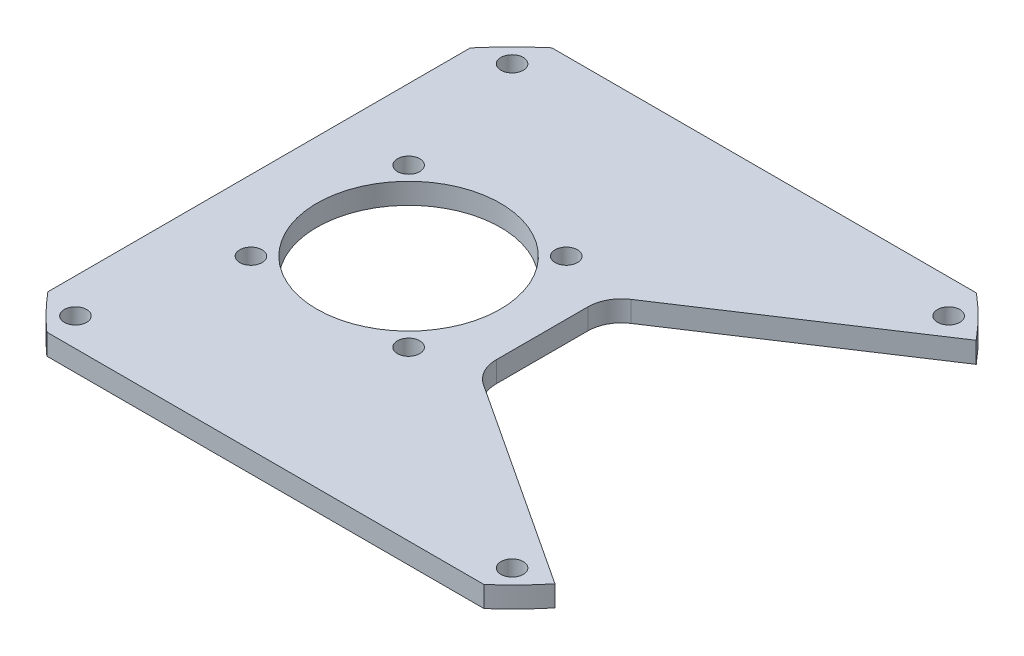
SolidWorks part; units mm, degrees
ref_plane "Front Plane" through (0, 0, 0) normal (0, 0, 1) x (1, 0, 0)
ref_plane "Top Plane" through (0, 0, 0) normal (0, 1, 0) x (1, 0, 0)
ref_plane "Right Plane" through (0, 0, 0) normal (1, 0, 0) x (0, 0, -1)
sketch "Sketch1" plane through (0, 0, 0) normal (0, 1, 0) x (1, 0, 0)
  line L0 (-38.5095, 32.1488) -> (-38.5095, -32.1488)
  line L1 (-33.2269, 33.2269) -> (33.2269, 33.2269) construction
  line L2 (-33.2269, 33.2269) -> (-33.2269, -33.2269) construction
  line L3 (-33.2269, -33.2269) -> (33.2269, -33.2269) construction
  line L4 (33.2269, 33.2269) -> (33.2269, -33.2269) construction
  line L5 (-33.2269, 33.2269) -> (33.2269, -33.2269) construction
  line L6 (-33.2269, -33.2269) -> (33.2269, 33.2269) construction
  line L7 (-27.748, 12) -> (-3.748, 12) construction
  line L8 (-27.748, 12) -> (-27.748, -12) construction
  line L9 (-27.748, -12) -> (-3.748, -12) construction
  line L10 (-3.748, 12) -> (-3.748, -12) construction
  line L11 (-27.748, 12) -> (-3.748, -12) construction
  line L12 (-27.748, -12) -> (-3.748, 12) construction
  line L13 (-33.274, -37.5416) -> (33.274, -37.5416)
  line L14 (-32.3186, 38.3671) -> (32.3186, 38.3671)
  line L15 (4.572, 9.721) -> (4.572, -9.721)
  line L16 (4.572, -9.721) -> (38.5873, -32.0554)
  line L17 (4.572, 9.721) -> (38.5414, 32.1106)
  circle A0 centre (0, 0) radius 50.165 construction
  circle A1 centre (-15.748, 0) radius 13.97
  arc A2 (38.5873, -32.0554) -> (33.274, -37.5416) centre (0, 0) cw
  arc A3 (38.5414, 32.1106) -> (32.3186, 38.3671) centre (0, 0) ccw
  arc A4 (-32.3186, 38.3671) -> (-38.5095, 32.1488) centre (0, 0) ccw
  arc A5 (-33.274, -37.5416) -> (-38.5095, -32.1488) centre (0, 0) cw
  point P15 (4.572, 0)
  point P17 (8.9369, 11.938)
  point P22 (-38.5095, 0)
  point P24 (-38.5095, 32.1488)
  point P25 (38.5873, -32.1488)
  point P26 (38.5873, 32.1488)
  point P28 (0, 0)
  dimension "D1" = 100.33
  dimension "D2" = 27.94
  dimension "D3" = 15.748
  dimension "D4" = 93.98
  dimension "D5" = 24
  dimension "D6" = 20.32
extrude "Boss-Extrude1" add sketch "Sketch1" along normal mid plane 3.175
fillet "Fillet1" radius 5.08 2 edges at (4.572, 0, -9.721) (4.572, 0, 9.721)
hole_wizard "M3 Clearance Hole1" positions "Sketch2" profile "Sketch3" hole size "M3" standard "ISO" end condition through all
sketch "Sketch2" plane through (0, 1.5875, 0) normal (0, 1, 0) x (1, 0, 0)
  point P0 (-33.2269, 33.2269)
  point P3 (33.2269, 33.2269)
  point P6 (33.2269, -33.2269)
  point P9 (-33.2269, -33.2269)
sketch "Sketch3" plane through (-33.2269, 1.5875, -33.2269) normal (1, 0, 0) x (0, 0, 1)
  line L0 (0, 0) -> (0, 3.175)
  line L1 (0, 3.175) -> (1.7, 3.175)
  line L2 (1.7, 3.175) -> (1.7, 0)
  line L5 (1.7, 0) -> (0, 0)
  line L11 (0, -6.35) -> (0, 107.95) construction
  dimension "Thru Hole Dia." = 3.4
  dimension "Thru Hole Depth" = 3.175
hole_wizard "M3 Clearance Hole2" positions "Sketch4" profile "Sketch5" hole size "M3" standard "ISO" end condition through all
sketch "Sketch4" plane through (0, 1.5875, 0) normal (0, 1, 0) x (1, 0, 0)
  point P0 (-27.748, 12)
  point P3 (-3.748, 12)
  point P6 (-3.748, -12)
  point P9 (-27.748, -12)
sketch "Sketch5" plane through (-27.748, 1.5875, -12) normal (1, 0, 0) x (0, 0, 1)
  line L0 (0, 0) -> (0, 3.175)
  line L1 (0, 3.175) -> (1.7, 3.175)
  line L2 (1.7, 3.175) -> (1.7, 0)
  line L5 (1.7, 0) -> (0, 0)
  line L11 (0, -6.35) -> (0, 107.95) construction
  dimension "Thru Hole Dia." = 3.4
  dimension "Thru Hole Depth" = 3.175
